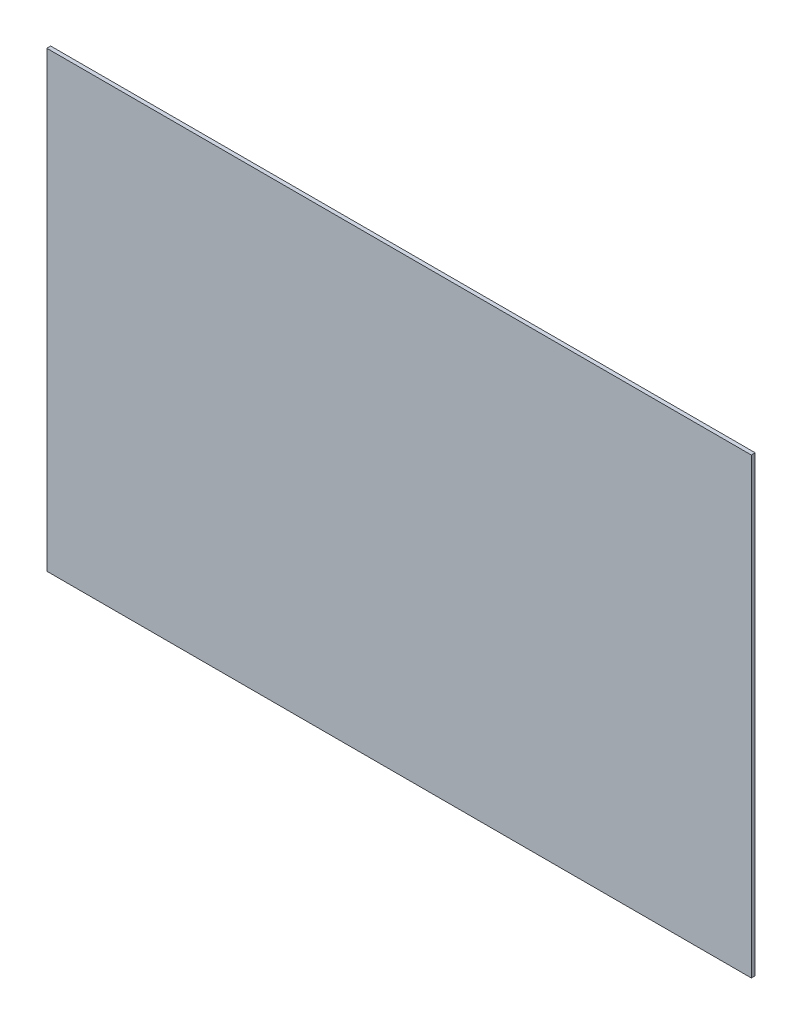
SolidWorks part; units mm, degrees
ref_plane "前视基准面" through (0, 0, 0) normal (0, 0, 1) x (1, 0, 0)
ref_plane "上视基准面" through (0, 0, 0) normal (0, 1, 0) x (1, 0, 0)
ref_plane "右视基准面" through (0, 0, 0) normal (1, 0, 0) x (0, 0, -1)
sketch "草图1" plane through (0, 0, 0) normal (0, 0, 1) x (1, 0, 0)
  line L1 (-91, 58.5) -> (91, 58.5)
  line L2 (-91, 58.5) -> (-91, -58.5)
  line L3 (-91, -58.5) -> (91, -58.5)
  line L4 (91, 58.5) -> (91, -58.5)
  line L5 (-91, 58.5) -> (91, -58.5) construction
  line L6 (-91, -58.5) -> (91, 58.5) construction
  point P0 (0, 0)
  dimension "D1" = 182
  dimension "D2" = 117
extrude "凸台-拉伸1" add sketch "草图1" along normal blind 1
